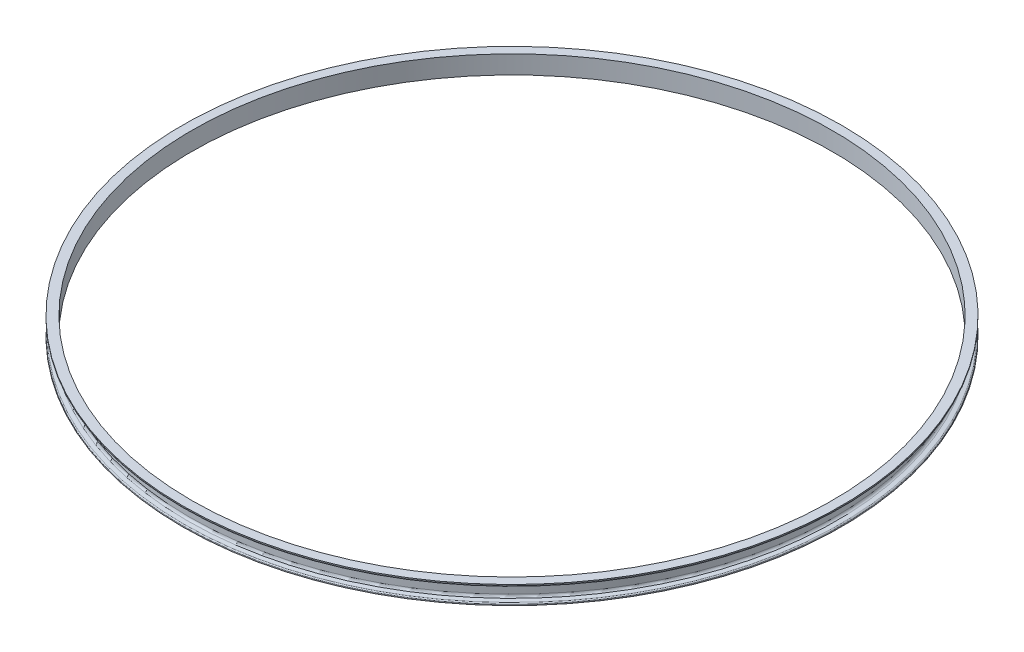
SolidWorks part; units mm, degrees
material "ASTM A36 Steel"
ref_plane "Front Plane" through (0, 0, 0) normal (0, 0, 1) x (1, 0, 0)
ref_plane "Top Plane" through (0, 0, 0) normal (0, 1, 0) x (1, 0, 0)
ref_plane "Right Plane" through (0, 0, 0) normal (1, 0, 0) x (0, 0, -1)
sketch "Sketch1" plane through (0, 0, 0) normal (0, 0, 1) x (1, 0, 0)
  line L0 (0, 0) -> (0, 40)
  line L1 (0, 40) -> (20, 40)
  line L2 (0, 0) -> (20, 0)
  line L5 (-700, 40) -> (-700, -268.2261) construction
  line L12 (5, 29.0143) -> (5, 10.9857)
  line L15 (20, 40) -> (20, 37.8679)
  line L16 (20, 0) -> (20, 2.1321)
  line L17 (9.1779, 33.9463) -> (17.911, 35.4019)
  line L18 (9.1779, 6.0537) -> (17.911, 4.5981)
  arc A9 (5, 10.9857) -> (9.1779, 6.0537) centre (10, 10.9857) ccw
  arc A10 (5, 29.0143) -> (9.1779, 33.9463) centre (10, 29.0143) cw
  arc A11 (20, 37.8679) -> (17.911, 35.4019) centre (17.5, 37.8679) cw
  arc A12 (20, 2.1321) -> (17.911, 4.5981) centre (17.5, 2.1321) ccw
revolve "Revolve1" add sketch "Sketch1" angle 360 about L5
